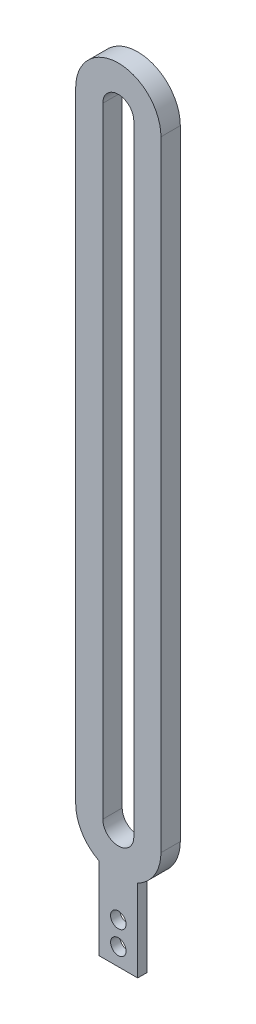
SolidWorks part; units mm, degrees
ref_plane "Front Plane" through (0, 0, 0) normal (0, 0, 1) x (1, 0, 0)
ref_plane "Top Plane" through (0, 0, 0) normal (0, 1, 0) x (1, 0, 0)
ref_plane "Right Plane" through (0, 0, 0) normal (1, 0, 0) x (0, 0, -1)
sketch "Sketch1" plane through (0, 0, 0) normal (0, 0, 1) x (1, 0, 0)
  line L4 (-4, -160) -> (-4, 0)
  line L5 (4, 0) -> (4, -160)
  line L17 (-4, -160) -> (4, -160) construction
  line L18 (11, 0) -> (11, -160)
  line L19 (-11, -160) -> (-11, 0)
  arc A4 (-4, 0) -> (4, 0) centre (0, 0) cw
  arc A6 (-4, -160) -> (4, -160) centre (0, -160) ccw
  arc A7 (-11, -160) -> (11, -160) centre (0, -160) ccw
  arc A8 (-11, 0) -> (11, 0) centre (0, 0) cw
  point P16 (-4, -80)
  dimension "D1" = 7
  dimension "D2" = 8
  dimension "D5" = 160
extrude "Boss-Extrude1" add sketch "Sketch1" along normal blind 5
sketch "Sketch2" plane through (0, 0, 5) normal (0, 0, 1) x (1, 0, 0)
  line L0 (0, -171) -> (0, -187.3337) construction
  line L1 (-5, -171) -> (-5, -169.798)
  line L3 (-5, -171) -> (-5, -191)
  line L4 (-5, -191) -> (5, -191)
  line L5 (5, -171) -> (5, -191)
  line L6 (-5, -171) -> (5, -191) construction
  line L7 (-5, -191) -> (5, -171) construction
  line L8 (5, -171) -> (5, -169.798)
  line L9 (-5, -171) -> (5, -171) construction
  line L10 (11, -160) -> (11, 0)
  line L11 (-11, 0) -> (-11, -160)
  arc A0 (-11, -160) -> (11, -160) centre (0, -160) ccw construction
  arc A3 (-11, -160) -> (11, -160) centre (0, -160) ccw
  arc A4 (11, 0) -> (-11, 0) centre (0, 0) ccw
  arc A5 (-5, -169.798) -> (5, -169.798) centre (0, -160) ccw
  point P7 (0, -181)
  dimension "D2" = 20
  dimension "D3" = 10
  dimension "D1" = 0
extrude "Boss-Extrude2" add sketch "Sketch2" against normal blind 2.4
sketch "Sketch3" plane through (0, 0, 2.6) normal (0, 0, -1) x (-1, 0, 0)
  line L0 (0, -191) -> (0, -171) construction
  line L1 (5, -191) -> (-5, -191) construction
  arc A0 (-5, -169.798) -> (5, -169.798) centre (0, -160) ccw construction
  circle A1 centre (0, -186.5) radius 2
  circle A2 centre (0, -180.5) radius 2
  dimension "D1" = 4
  dimension "D2" = 4
  dimension "D3" = 6
  dimension "D4" = 4.5
extrude "Cut-Extrude1" cut sketch "Sketch3" against normal blind 2.4
